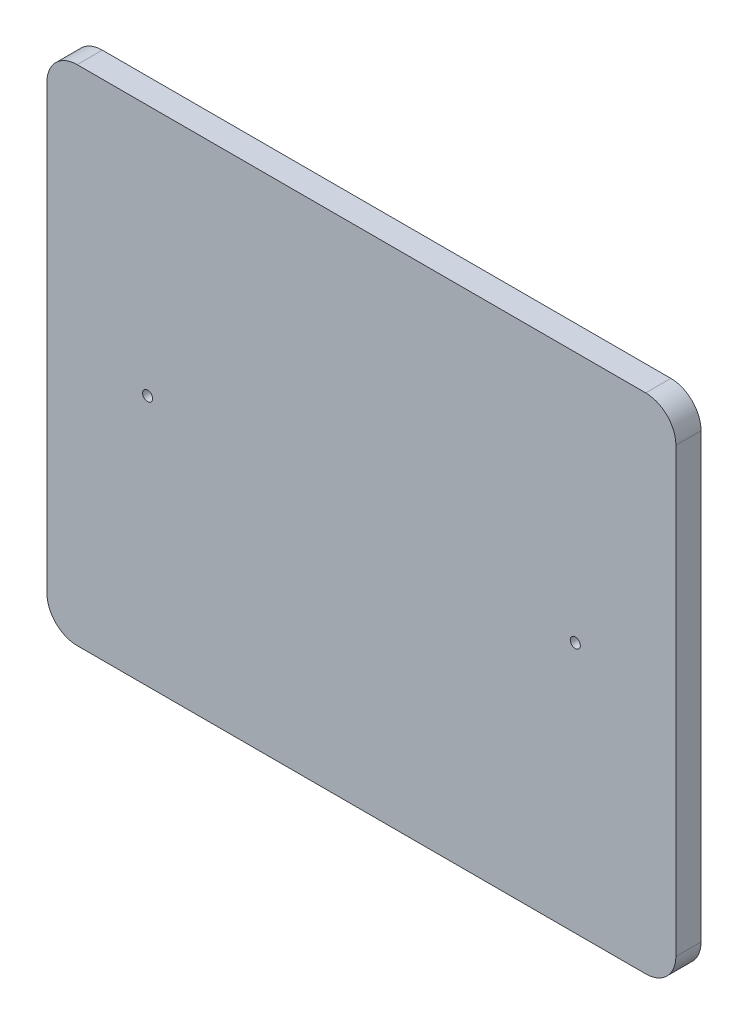
SolidWorks part; units mm, degrees
material "Balsa"
ref_plane "Alzado" through (0, 0, 0) normal (0, 0, 1) x (1, 0, 0)
ref_plane "Planta" through (0, 0, 0) normal (0, 1, 0) x (1, 0, 0)
ref_plane "Vista lateral" through (0, 0, 0) normal (1, 0, 0) x (0, 0, -1)
sketch "Croquis1" plane through (0, 0, 0) normal (0, 0, 1) x (1, 0, 0)
  line L0 (-121.0847, -96.8678) -> (-125, -100) construction
  line L1 (113, -100) -> (-113, -100)
  line L2 (125, -88) -> (125, 88)
  line L3 (113, 100) -> (-113, 100)
  line L4 (-125, -88) -> (-125, 88)
  line L5 (125, -100) -> (121.0847, -96.8678) construction
  line L6 (125, 100) -> (121.0847, 96.8678) construction
  line L7 (-121.0847, 96.8678) -> (-125, 100) construction
  line L8 (0, 100) -> (0, -100) construction
  line L9 (-125, 0) -> (125, 0) construction
  arc A0 (125, 88) -> (113, 100) centre (113, 88) ccw
  arc A1 (125, -88) -> (113, -100) centre (113, -88) cw
  arc A2 (-113, -100) -> (-125, -88) centre (-113, -88) cw
  arc A3 (-125, 88) -> (-113, 100) centre (-113, 88) cw
  point P0 (0, 0)
  dimension "D3" = 12
  dimension "D1" = 250
  dimension "D2" = 200
extrude "Saliente-Extruir1" add sketch "Croquis1" along normal blind 10
sketch "Croquis2" plane through (0, 0, 10) normal (0, 0, 1) x (1, 0, 0)
  line L0 (0, 100) -> (0, -100) construction
  line L1 (113, 100) -> (-113, 100) construction
  line L2 (-113, -100) -> (113, -100) construction
  line L3 (-125, 0) -> (125, 0) construction
  line L4 (-125, 88) -> (-125, -88) construction
  line L5 (125, -88) -> (125, 88) construction
  circle A0 centre (-85, 0) radius 2
  circle A1 centre (85, 0) radius 2
  dimension "D1" = 4
  dimension "D2" = 170
extrude "Cortar-Extruir1" cut sketch "Croquis2" against normal blind 10 contours A0 | A1
